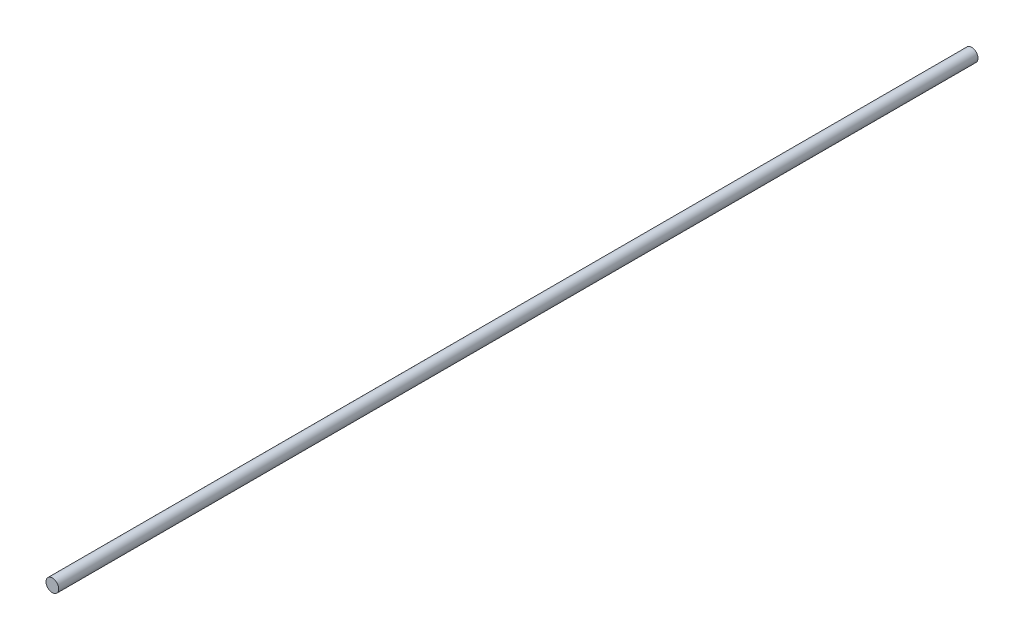
SolidWorks part; units mm, degrees
ref_plane "Front" through (0, 0, 0) normal (0, 0, 1) x (1, 0, 0)
ref_plane "Top" through (0, 0, 0) normal (0, 1, 0) x (1, 0, 0)
ref_plane "Right" through (0, 0, 0) normal (1, 0, 0) x (0, 0, -1)
sketch "Sketch1" plane through (0, 0, 0) normal (0, 0, 1) x (1, 0, 0)
  circle A0 centre (0, 0) radius 3.175
  dimension "D1" = 6.35
extrude "Boss-Extrude1" add sketch "Sketch1" along normal mid plane 457.2
